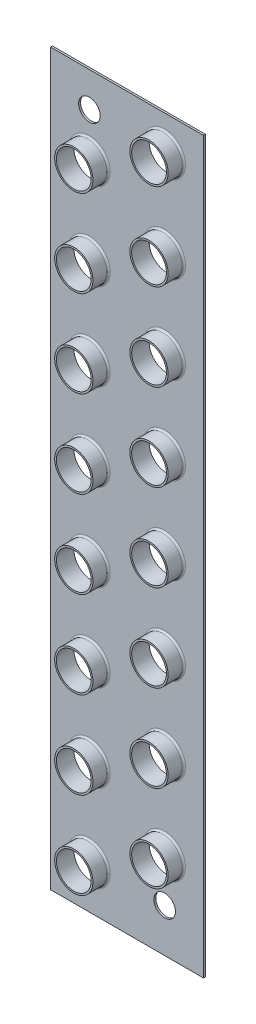
SolidWorks part; units mm, degrees
material "1060 Alloy"
ref_plane "Front Plane" through (0, 0, 0) normal (0, 0, 1) x (1, 0, 0)
ref_plane "Top Plane" through (0, 0, 0) normal (0, 1, 0) x (1, 0, 0)
ref_plane "Right Plane" through (0, 0, 0) normal (1, 0, 0) x (0, 0, -1)
sketch "Sketch2" plane through (0, 0, 0) normal (0, 0, 1) x (1, 0, 0)
  line L1 (0, 0) -> (44, 0)
  line L2 (0, 0) -> (0, -210)
  line L3 (0, -210) -> (44, -210)
  line L4 (44, 0) -> (44, -210)
  dimension "D1" = 210
  dimension "D2" = 44
extrude "Boss-Extrude1" add sketch "Sketch2" along normal blind 0.55
sketch "Sketch3" plane through (0, 0, 0.55) normal (0, 0, 1) x (1, 0, 0)
  line L0 (44, 0) -> (0, 0) construction
  line L1 (22, 0) -> (22, -30.9191) construction
  line L2 (11.1747, -22.5) -> (32.8253, -22.5) construction
  circle A0 centre (11.1747, -22.5) radius 5
  circle A1 centre (32.8253, -10) radius 5
  point P8 (22, -22.5)
  dimension "D1" = 10
  dimension "D2" = 10
  dimension "D3" = 10
  dimension "D4" = 12.5
  dimension "D5" = 25
extrude "Cut-Extrude1" cut sketch "Sketch3" against normal through all both and the other way through all
sketch "Sketch5" plane through (0, 0, 0.55) normal (0, 0, 1) x (1, 0, 0)
  circle A0 centre (11.1747, -22.5) radius 5.5
  circle A1 centre (32.8253, -10) radius 5
  circle A2 centre (32.8253, -10) radius 5
  circle A3 centre (11.1747, -22.5) radius 5
  circle A4 centre (11.1747, -22.5) radius 5
  circle A5 centre (32.8253, -10) radius 5.5
  dimension "D1" = 0
  dimension "D2" = 0
  dimension "D3" = 0.5
extrude "Boss-Extrude2" add sketch "Sketch5" along normal blind 4.5
fillet "Fillet1" radius 0.5 2 edges at (16.6747, -22.5, 0.55) (38.3253, -10, 0.55)
pattern_linear "LPattern1" count 8 spacing 25 along (0, -1, 0) of "Boss-Extrude2", "Cut-Extrude1", "Fillet1"
sketch "Sketch6" plane through (0, 0, 0) normal (0, 0, -1) x (-1, 0, 0)
  line L0 (-11.1747, -10) -> (-32.8253, -10) construction
  line L1 (-11.1747, -10) -> (-11.1747, -22.5) construction
  line L2 (-32.8253, -197.5) -> (-11.1747, -197.5) construction
  line L3 (-32.8253, -197.5) -> (-32.8253, -185) construction
  circle A0 centre (-11.1747, -10) radius 3.1
  circle A1 centre (-32.8253, -197.5) radius 3.1
  dimension "D1" = 6.2
  dimension "D2" = 6.2
extrude "Cut-Extrude2" cut sketch "Sketch6" against normal through all
